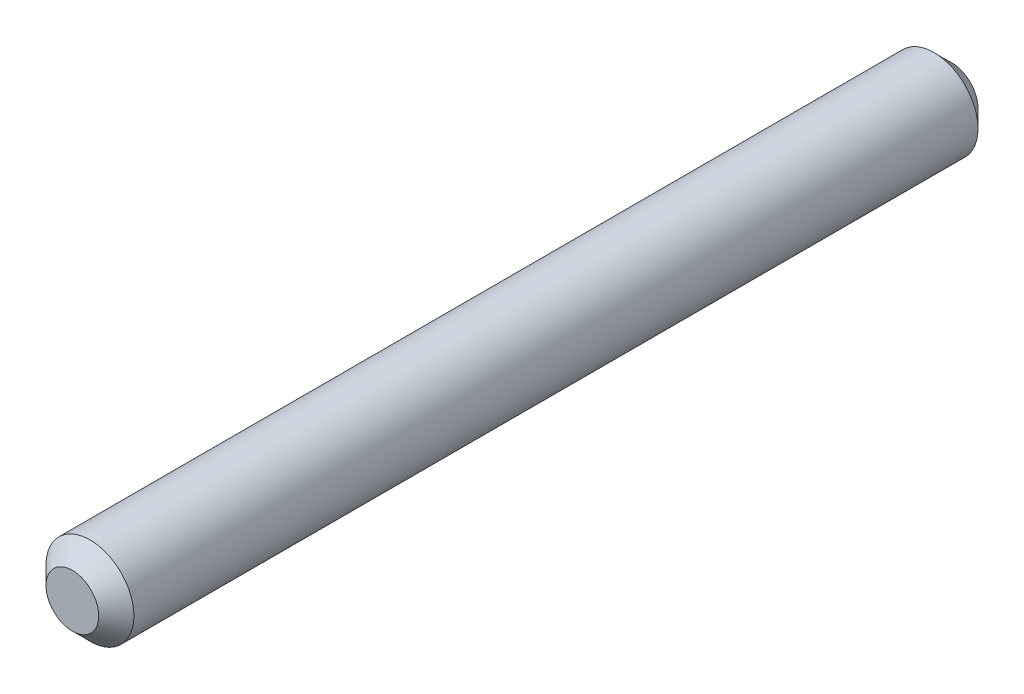
SolidWorks part; units mm, degrees
material "Alloy Steel"
ref_plane "Front Plane" through (0, 0, 0) normal (0, 0, 1) x (1, 0, 0)
ref_plane "Top Plane" through (0, 0, 0) normal (0, 1, 0) x (1, 0, 0)
ref_plane "Right Plane" through (0, 0, 0) normal (1, 0, 0) x (0, 0, -1)
sketch "Sketch1" plane through (0, 0, 0) normal (0, 0, 1) x (1, 0, 0)
  circle A0 centre (0, 0) radius 6.35
  dimension "D1" = 12.7
extrude "Boss-Extrude1" add sketch "Sketch1" against normal blind 127
chamfer "Chamfer1" distance 2.54 angle 45 2 edges at (6.35, 0, -127) (6.35, 0, 0)
